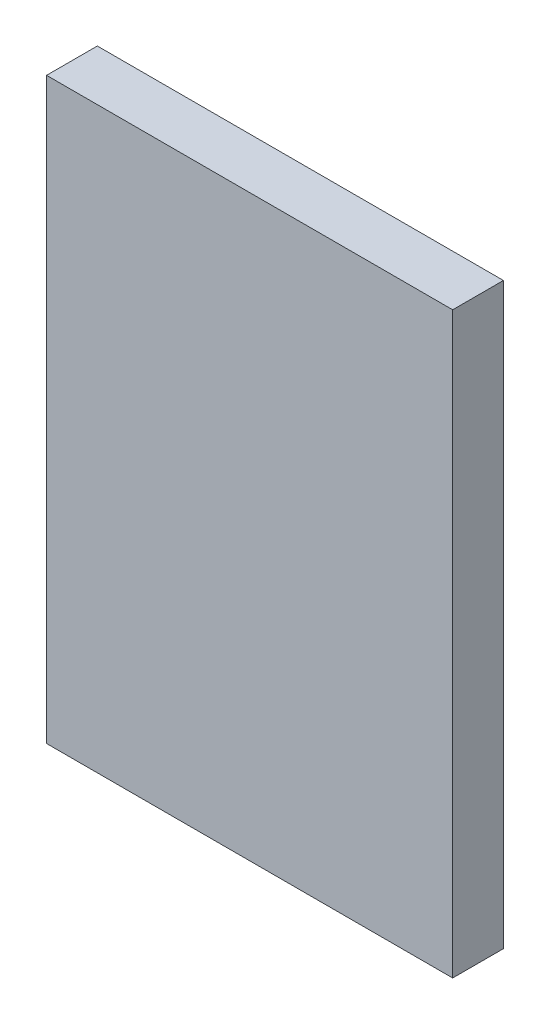
SolidWorks part; units mm, degrees
ref_plane "Спереди" through (0, 0, 0) normal (0, 0, 1) x (1, 0, 0)
ref_plane "Сверху" through (0, 0, 0) normal (0, 1, 0) x (1, 0, 0)
ref_plane "Справа" through (0, 0, 0) normal (1, 0, 0) x (0, 0, -1)
sketch "Эскиз1" plane through (0, 0, 0) normal (0, 0, 1) x (1, 0, 0)
  line L0 (-20, -28.5) -> (-20, 28.5)
  line L1 (-20, 28.5) -> (20, 28.5)
  line L2 (20, 28.5) -> (20, -28.5)
  line L3 (20, -28.5) -> (-20, -28.5)
  line L4 (-20, 28.5) -> (20, -28.5) construction
  line L5 (-20, -28.5) -> (20, 28.5) construction
  point P5 (0, 0)
  dimension "D1" = 40
  dimension "D2" = 57
extrude "Бобышка-Вытянуть1" add sketch "Эскиз1" against normal blind 5
sketch "Эскиз2" plane through (0, 0, 0) normal (0, 0, 1) x (1, 0, 0)
  line L0 (0, 0) -> (0, -37.6405) construction
